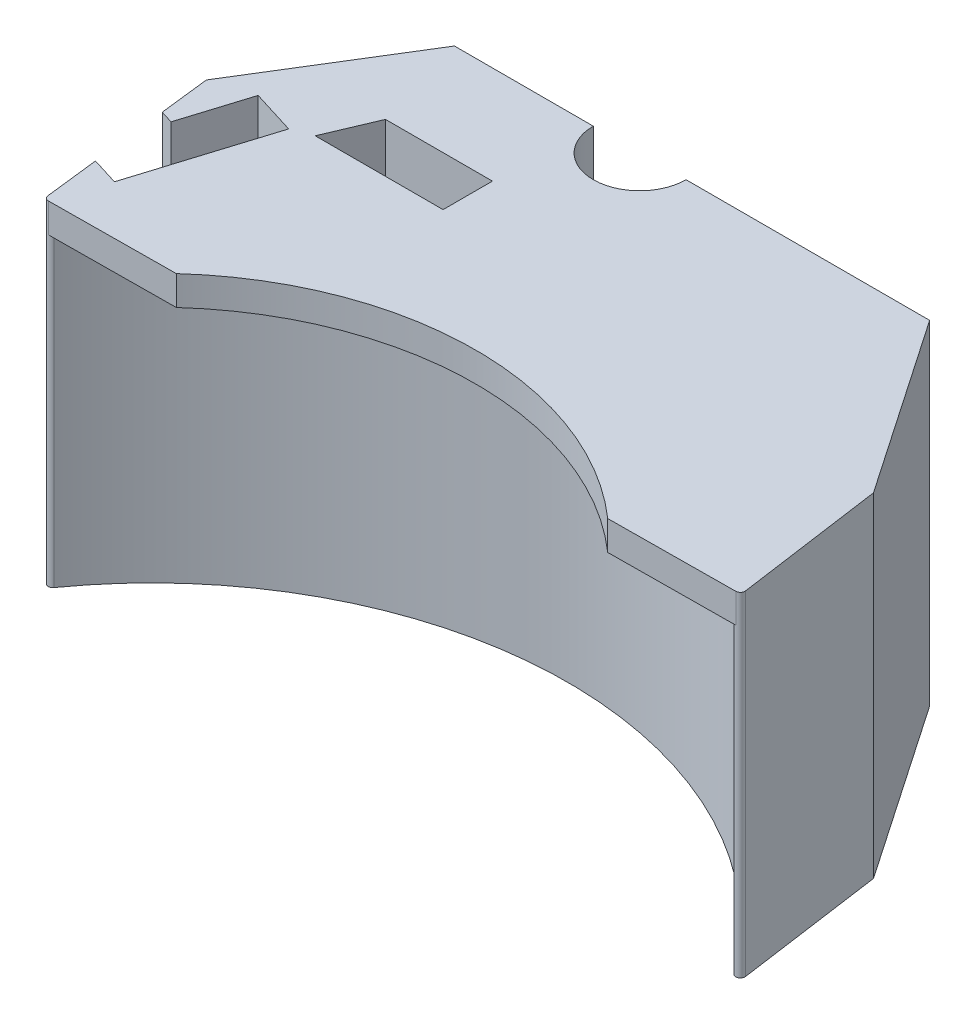
SolidWorks part; units mm, degrees
material "Custom Plastic"
ref_plane "X-Y Datum" through (0, 0, 0) normal (0, 0, 1) x (1, 0, 0)
ref_plane "X-Z Datum" through (0, 0, 0) normal (0, 1, 0) x (1, 0, 0)
ref_plane "Y-Z Datum" through (0, 0, 0) normal (1, 0, 0) x (0, 0, -1)
sketch "Sketch3" plane through (0, 0, 0) normal (0, 1, 0) x (1, 0, 0)
  line L3 (-475.1548, -2.1008) -> (-513.1532, -2.1008)
  line L5 (-349.8587, -50.677) -> (-343.3869, -96.6484)
  line L6 (-449.7548, -2.1008) -> (-383.0603, -2.1008)
  line L7 (-383.0603, -2.1008) -> (-349.8587, -50.677)
  line L8 (-532.9131, -96.6484) -> (-539.0648, -44.1168)
  line L9 (-539.0648, -44.1168) -> (-513.1532, -2.1008)
  line L10 (-475.1548, -2.1008) -> (-449.7548, -2.1008) construction
  line L11 (-532.9131, -96.6484) -> (-343.3869, -96.6484) construction
  circle A0 centre (-438.15, -160.02) radius 114 construction
  arc A1 (-324.3062, -165.9863) -> (-551.9938, -154.0537) centre (-438.15, -160.02) ccw construction
  arc A2 (-343.3869, -96.6484) -> (-532.9131, -96.6484) centre (-438.15, -160.02) ccw
  arc A3 (-475.1548, -2.1008) -> (-449.7548, -2.1008) centre (-462.4548, -2.1008) ccw
  arc A4 (-471.9814, -10.4992) -> (-451.2668, -8.1108) centre (-462.4548, -2.1008) ccw construction
  point P9 (-343.3869, -96.6484)
  point P14 (-349.8587, -50.677)
extrude "Boss-Extrude1" add sketch "Sketch3" against normal blind 76.2 and the other way blind 15.24
fillet "Fillet1" radius 1.27 2 edges at (-343.3869, -30.48, 96.6484) (-532.9131, -30.48, 96.6484)
sketch "Sketch4" plane through (0, 15.24, 0) normal (0, 1, 0) x (1, 0, 0)
  line L1 (-380.1355, -93.162) -> (-345.3692, -92.8733)
  line L2 (-497.2668, -94.1346) -> (-532.0332, -94.4233)
  arc A0 (-532.0332, -94.4233) -> (-345.3692, -92.8733) centre (-438.1576, -159.1043) cw
  arc A2 (-497.2668, -94.1346) -> (-380.1355, -93.162) centre (-438.1576, -159.1043) cw
  arc A4 (-533.3051, -93.3011) -> (-531.0092, -93.8901) centre (-532.0437, -93.1533) ccw construction
  arc A5 (-346.4018, -92.3571) -> (-344.1221, -91.4263) centre (-345.3797, -91.6033) ccw construction
  point P3 (0, 0)
  point P6 (0, 0)
  point P8 (-529.1189, -91.313)
  point P16 (0, 0)
  point P17 (-348.2293, -89.9467)
  point P19 (0, 0)
  point P24 (0, 0)
  point P25 (0, 0)
extrude "Boss-Extrude2" add sketch "Sketch4" against normal up to surface (8.04 mm away)
sketch "Sketch5" plane through (0, 15.24, 0) normal (0, 1, 0) x (1, 0, 0)
  line L0 (-528.3141, -40.6898) -> (-516.1875, -44.4628)
  line L1 (-516.1875, -44.4628) -> (-527.5066, -80.8426)
  line L2 (-527.5066, -80.8426) -> (-695.2326, -28.6567)
  line L3 (-528.3141, -40.6898) -> (-533.9736, -58.8796)
  line L4 (-533.9736, -58.8796) -> (-689.573, -10.4668)
  line L6 (-682.027, 13.7864) -> (-689.573, -10.4668) construction
  circle A2 centre (-685.8, 1.6598) radius 12.7 construction
  arc A3 (-684.6727, -10.9901) -> (-673.3556, 4.1948) centre (-685.8, 1.6598) ccw construction
  arc A4 (-682.027, 13.7864) -> (-689.573, -10.4668) centre (-685.8, 1.6598) ccw
  arc A5 (-671.6541, 30.0844) -> (-695.2326, -28.6567) centre (-685.8, 1.6598) ccw
  arc A6 (-682.027, 13.7864) -> (-671.6541, 30.0844) centre (-677.0115, 22.0442) ccw
  dimension "D1" = 19.05
  dimension "D2" = 38.1
  dimension "D3" = 12.7
extrude "Cut-Extrude1" cut sketch "Sketch5" against normal blind 50.8
sketch "Sketch6" plane through (0, 15.24, 0) normal (0, 1, 0) x (1, 0, 0)
  line L0 (-505.1995, -28.9416) -> (-510.9242, -42.4549)
  line L1 (-505.1995, -28.9416) -> (-475.9187, -28.9416)
  line L2 (-475.9187, -28.9416) -> (-475.9187, -42.4549)
  line L3 (-475.9187, -42.4549) -> (-510.9242, -42.4549)
extrude "Cut-Extrude2" cut sketch "Sketch6" against normal blind 38.1
sketch "Sketch7" plane through (0, -76.2, 0) normal (0, -1, 0) x (1, 0, 0)
  line L4 (-477.7843, 30.7504) -> (-493.2979, 29.5925)
  line L5 (-512.959, 54.0747) -> (-477.7843, 43.4991)
  line L6 (-477.7843, 43.4991) -> (-477.7843, 30.7504)
  arc A0 (-512.959, 54.0747) -> (-493.2979, 29.5925) centre (-494.7157, 48.5897) ccw
  arc A1 (-512.959, 54.0747) -> (-493.2979, 29.5925) centre (-494.7157, 48.5897) ccw construction
extrude "Cut-Extrude3" cut sketch "Sketch7" against normal blind 38.1
sketch "Sketch8" plane through (0, 0, 0) normal (0, 1, 0) x (1, 0, 0)
  line L1 (-547.6308, 25.0338) -> (-327.6308, 25.0338)
  line L2 (-547.6308, 25.0338) -> (-547.6308, -194.9662)
  line L3 (-547.6308, -194.9662) -> (-327.6308, -194.9662)
  line L4 (-327.6308, 25.0338) -> (-327.6308, -194.9662)
  line L5 (-437.6308, -194.9662) -> (-437.6308, 25.0338) construction
  line L6 (-547.6308, -84.9662) -> (-327.6308, -84.9662) construction
  point P76 (-437.6308, -84.9662)
  dimension "D1" = 220
